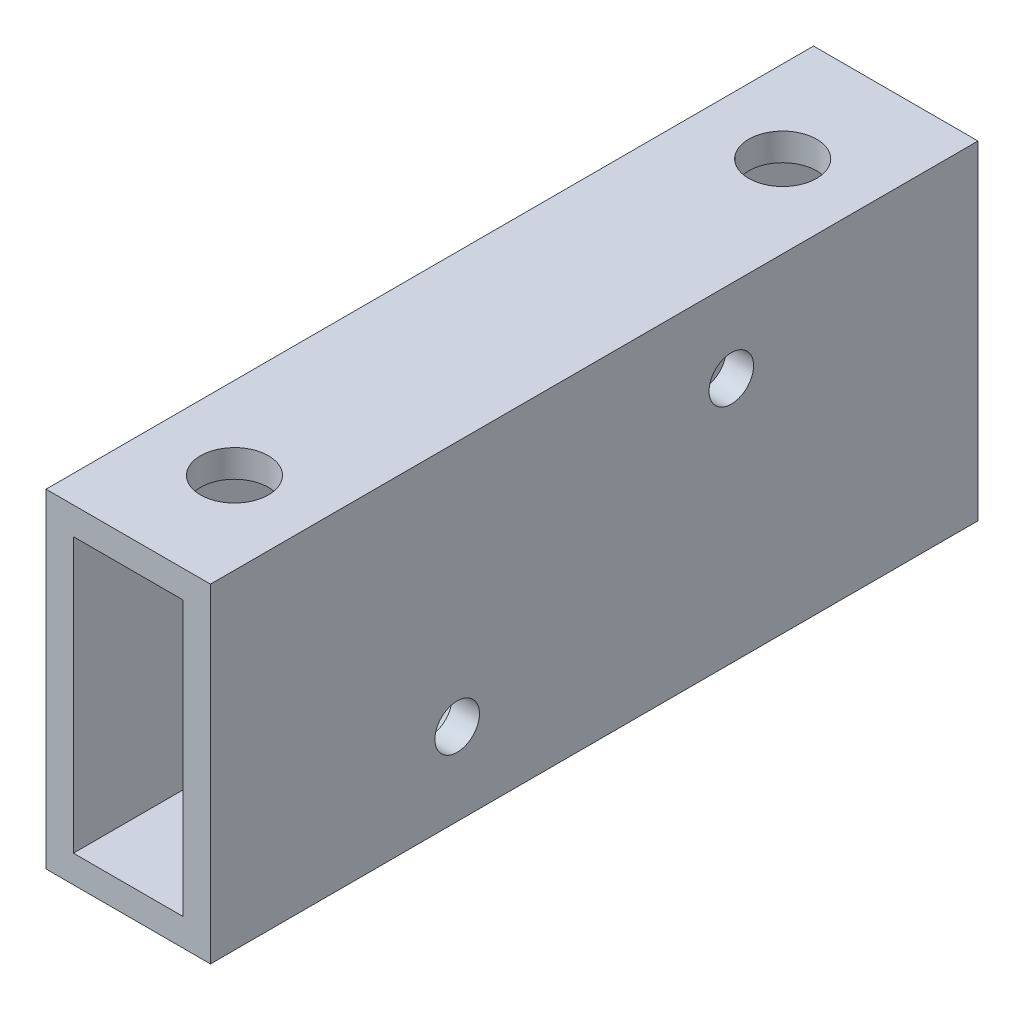
SolidWorks part; units mm, degrees
ref_plane "Front Plane" through (0, 0, 0) normal (0, 0, 1) x (1, 0, 0)
ref_plane "Top Plane" through (0, 0, 0) normal (0, 1, 0) x (1, 0, 0)
ref_plane "Right Plane" through (0, 0, 0) normal (1, 0, 0) x (0, 0, -1)
sketch "Sketch1" plane through (0, 0, 0) normal (0, 0, 1) x (1, 0, 0)
  line L0 (6.35, -15.875) -> (6.35, 15.875)
  line L1 (-9.525, -19.05) -> (9.525, -19.05)
  line L2 (-9.525, -19.05) -> (-9.525, 19.05)
  line L3 (-9.525, 19.05) -> (9.525, 19.05)
  line L4 (9.525, -19.05) -> (9.525, 19.05)
  line L5 (-9.525, -19.05) -> (9.525, 19.05) construction
  line L6 (-9.525, 19.05) -> (9.525, -19.05) construction
  line L7 (-6.35, 15.875) -> (6.35, 15.875)
  line L8 (-6.35, -15.875) -> (-6.35, 15.875)
  line L9 (-6.35, -15.875) -> (6.35, -15.875)
  point P0 (0, 0)
  dimension "D1" = 38.1
  dimension "D2" = 19.05
  dimension "D3" = 3.175
extrude "Boss-Extrude1" add sketch "Sketch1" along normal blind 88.9
sketch "Sketch2" plane through (0, 19.05, 0) normal (0, 1, 0) x (1, 0, 0)
  line L0 (0, -88.9) -> (0, -79.375) construction
  line L1 (9.525, -88.9) -> (-9.525, -88.9) construction
  line L2 (0, -76.5969) -> (0, -13.0969) construction
  circle A0 centre (0, -76.5969) radius 2.7781
  circle A1 centre (0, -13.0969) radius 2.7781
  dimension "D2" = 63.5
  dimension "D3" = 5.5562
  dimension "D1" = 9.525
extrude "Cut-Extrude1" cut sketch "Sketch2" against normal through all
sketch "Sketch3" plane through (0, 19.05, 0) normal (0, 1, 0) x (1, 0, 0)
  circle A0 centre (0, -76.5969) radius 3.937
  circle A1 centre (0, -13.0969) radius 3.937
  dimension "D1" = 7.874
extrude "Cut-Extrude2" cut sketch "Sketch3" against normal up to next
sketch "Sketch4" plane through (9.525, 0, 0) normal (1, 0, 0) x (0, 0, -1)
  circle A0 centre (-60.325, -9.525) radius 2.5797 construction
  circle A1 centre (-60.325, -9.525) radius 2.5797
  circle A2 centre (-28.575, 9.525) radius 2.5797 construction
  circle A3 centre (-28.575, 9.525) radius 2.5797
extrude "Cut-Extrude3" cut sketch "Sketch4" against normal up to next
